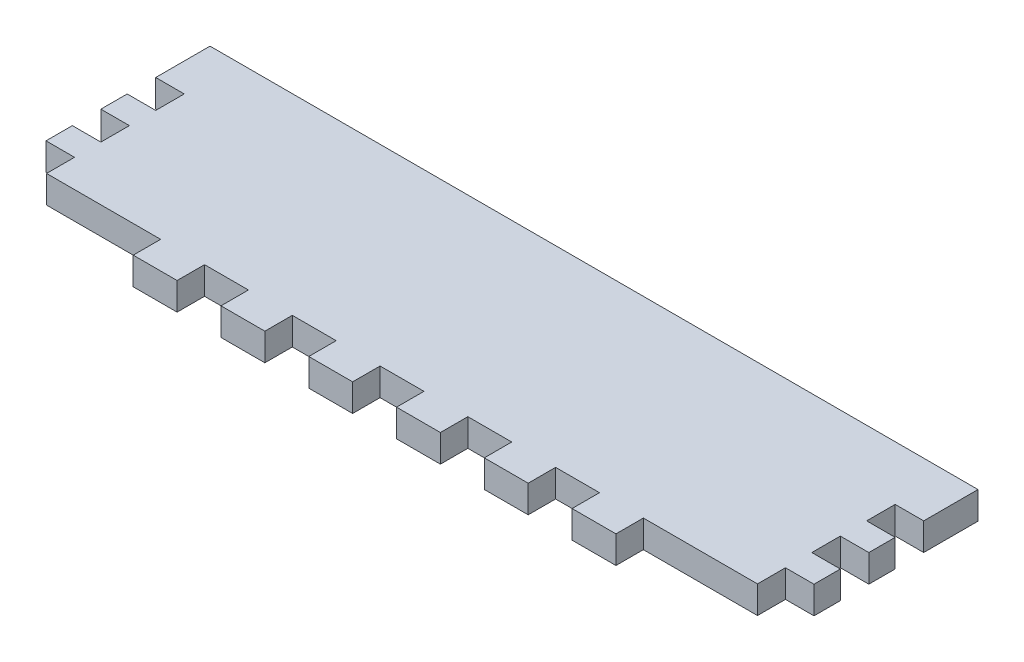
SolidWorks part; units mm, degrees
ref_plane "Front Plane" through (0, 0, 0) normal (0, 0, 1) x (1, 0, 0)
ref_plane "Top Plane" through (0, 0, 0) normal (0, 1, 0) x (1, 0, 0)
ref_plane "Right Plane" through (0, 0, 0) normal (1, 0, 0) x (0, 0, -1)
sketch "Sketch1" plane through (0, 0, 0) normal (0, 1, 0) x (1, 0, 0)
  line L1 (-44.45, -9.525) -> (44.45, -9.525)
  line L2 (-44.45, -9.525) -> (-44.45, 9.525)
  line L3 (-44.45, 9.525) -> (44.45, 9.525)
  line L4 (44.45, -9.525) -> (44.45, 9.525)
  line L5 (-44.45, -9.525) -> (44.45, 9.525) construction
  line L6 (-44.45, 9.525) -> (44.45, -9.525) construction
  point P0 (0, 0)
  dimension "D1" = 88.9
  dimension "D2" = 19.05
extrude "Boss-Extrude1" add sketch "Sketch1" along normal blind 3.175
sketch "Sketch2" plane through (0, 3.175, 0) normal (0, 1, 0) x (1, 0, 0)
  line L0 (-44.45, 9.525) -> (-44.45, -9.525) construction
  line L1 (-44.45, 6.4135) -> (-41.148, 6.4135)
  line L2 (-44.45, 6.4135) -> (-44.45, 3.1115)
  line L3 (-44.45, 3.1115) -> (-41.148, 3.1115)
  line L4 (-41.148, 6.4135) -> (-41.148, 3.1115)
  line L18 (-44.45, 0.0635) -> (-44.45, -3.2385)
  line L19 (-44.45, 0.0635) -> (-41.148, 0.0635)
  line L20 (-41.148, 0.0635) -> (-41.148, -3.2385)
  line L21 (-44.45, -3.2385) -> (-41.148, -3.2385)
  line L22 (-44.45, -6.2865) -> (-44.45, -9.5885)
  line L23 (-44.45, -6.2865) -> (-41.148, -6.2865)
  line L24 (-41.148, -6.2865) -> (-41.148, -9.5885)
  line L25 (-44.45, -9.5885) -> (-41.148, -9.5885)
  line L26 (44.45, 9.525) -> (-44.45, 9.525) construction
  line L27 (25.4, 6.4135) -> (25.4, 3.1115) [skipped]
  line L28 (25.4, 6.4135) -> (28.702, 6.4135) [skipped]
  line L29 (28.702, 6.4135) -> (28.702, 3.1115) [skipped]
  line L30 (25.4, 3.1115) -> (28.702, 3.1115) [skipped]
  line L31 (25.4, 0.0635) -> (25.4, -3.2385) [skipped]
  line L32 (25.4, 0.0635) -> (28.702, 0.0635) [skipped]
  line L33 (28.702, 0.0635) -> (28.702, -3.2385) [skipped]
  line L34 (25.4, -3.2385) -> (28.702, -3.2385) [skipped]
  line L35 (25.4, -6.2865) -> (25.4, -9.5885) [skipped]
  line L36 (25.4, -6.2865) -> (28.702, -6.2865) [skipped]
  line L37 (28.702, -6.2865) -> (28.702, -9.5885) [skipped]
  line L38 (25.4, -9.5885) -> (28.702, -9.5885) [skipped]
  line L39 (0, 0) -> (0, 9.9502) construction
  line L40 (44.45, -9.5885) -> (41.148, -9.5885)
  line L41 (41.148, -6.2865) -> (41.148, -9.5885)
  line L42 (44.45, -6.2865) -> (41.148, -6.2865)
  line L43 (44.45, -6.2865) -> (44.45, -9.5885)
  line L44 (44.45, -3.2385) -> (41.148, -3.2385)
  line L45 (41.148, 0.0635) -> (41.148, -3.2385)
  line L46 (44.45, 0.0635) -> (41.148, 0.0635)
  line L47 (44.45, 0.0635) -> (44.45, -3.2385)
  line L48 (41.148, 6.4135) -> (41.148, 3.1115)
  line L49 (44.45, 3.1115) -> (41.148, 3.1115)
  line L50 (44.45, 6.4135) -> (44.45, 3.1115)
  line L51 (44.45, 6.4135) -> (41.148, 6.4135)
  point P8 (-44.45, 4.7625)
  dimension "D1" = 2
  dimension "D2" = 3.302
  dimension "D3" = 3.302
  dimension "D5" = 4.7625
  dimension "D6" = 6.35
  dimension "D7" = 3.302
  dimension "D4" = 3
extrude "Cut-Extrude1" cut sketch "Sketch2" against normal through all
sketch "Sketch3" plane through (0, 0, 0) normal (0, 1, 0) x (1, 0, 0)
  line L0 (-41.148, -9.525) -> (41.148, -9.525) construction
  line L1 (-27.94, -9.525) -> (-22.86, -9.525)
  line L2 (-27.94, -9.525) -> (-27.94, -12.7)
  line L3 (-27.94, -12.7) -> (-22.86, -12.7)
  line L4 (-22.86, -9.525) -> (-22.86, -12.7)
  line L22 (0, 0) -> (17.78, 0) construction
  line L43 (-17.78, -9.525) -> (-12.7, -9.525)
  line L44 (-44.45, 9.525) -> (44.45, 9.525)
  line L45 (-44.45, 9.525) -> (-44.45, 12.7)
  line L46 (-44.45, 12.7) -> (44.45, 12.7)
  line L47 (44.45, 9.525) -> (44.45, 12.7)
  line L48 (-17.78, -9.525) -> (-17.78, -12.7)
  line L49 (-17.78, -12.7) -> (-12.7, -12.7)
  line L50 (-12.7, -9.525) -> (-12.7, -12.7)
  line L51 (-7.62, -9.525) -> (-2.54, -9.525)
  line L52 (-7.62, -9.525) -> (-7.62, -12.7)
  line L53 (-7.62, -12.7) -> (-2.54, -12.7)
  line L54 (-2.54, -9.525) -> (-2.54, -12.7)
  line L55 (2.54, -9.525) -> (7.62, -9.525)
  line L56 (2.54, -9.525) -> (2.54, -12.7)
  line L57 (2.54, -12.7) -> (7.62, -12.7)
  line L58 (7.62, -9.525) -> (7.62, -12.7)
  line L59 (12.7, -9.525) -> (17.78, -9.525)
  line L60 (12.7, -9.525) -> (12.7, -12.7)
  line L61 (12.7, -12.7) -> (17.78, -12.7)
  line L62 (17.78, -9.525) -> (17.78, -12.7)
  line L63 (22.86, -9.525) -> (27.94, -9.525)
  line L64 (22.86, -9.525) -> (22.86, -12.7)
  line L65 (22.86, -12.7) -> (27.94, -12.7)
  line L66 (27.94, -9.525) -> (27.94, -12.7)
  point P6 (-25.4, -9.525)
  dimension "D2" = 5.08
  dimension "D3" = 3.175
  dimension "D4" = 3.175
  dimension "D5" = 25.4
extrude "Boss-Extrude2" add sketch "Sketch3" along normal blind 3.175
